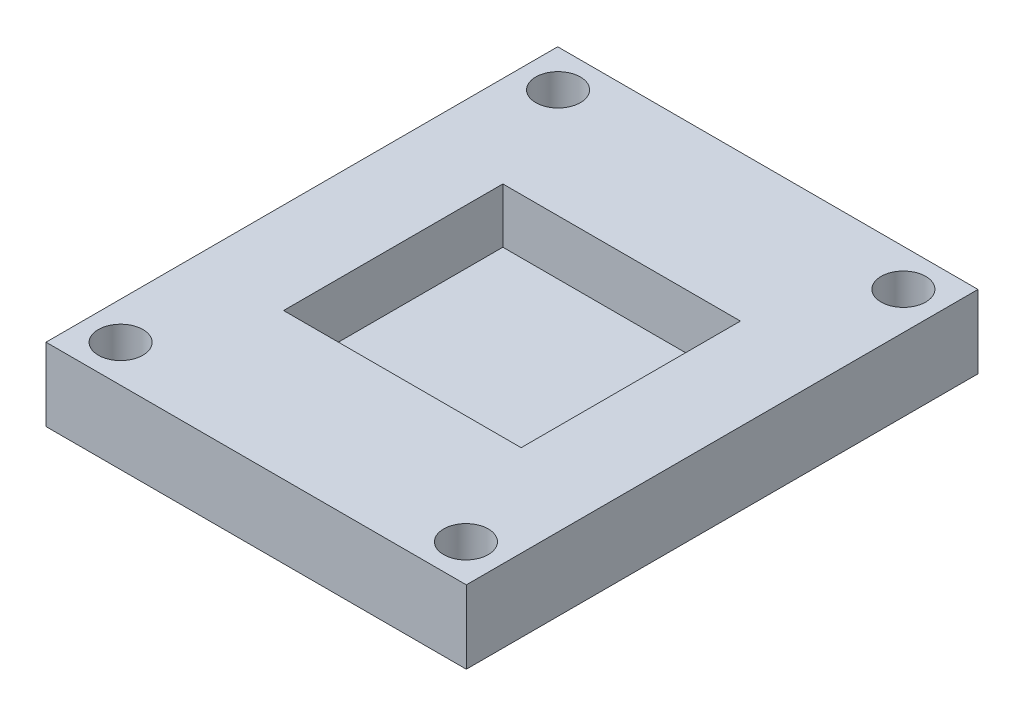
SolidWorks part; units mm, degrees
ref_plane "Front Plane" through (0, 0, 0) normal (0, 0, 1) x (1, 0, 0)
ref_plane "Top Plane" through (0, 0, 0) normal (0, 1, 0) x (1, 0, 0)
ref_plane "Right Plane" through (0, 0, 0) normal (1, 0, 0) x (0, 0, -1)
sketch "Sketch1" plane through (0, 0, 0) normal (0, 1, 0) x (1, 0, 0)
  line L0 (2.2113, 14.2748) -> (2.2113, -21.2852) construction
  line L1 (-12.3937, 14.2748) -> (16.8163, 14.2748)
  line L2 (-12.3937, 14.2748) -> (-12.3937, -21.2852)
  line L3 (-12.3937, -21.2852) -> (16.8163, -21.2852)
  line L4 (16.8163, 14.2748) -> (16.8163, -21.2852)
  line L5 (-12.3937, -3.5052) -> (16.8163, -3.5052) construction
  circle A0 centre (-9.7887, 11.6948) radius 1.55
  circle A1 centre (14.2113, 11.6948) radius 1.55
  circle A2 centre (14.2113, -18.7052) radius 1.55
  circle A3 centre (-9.7887, -18.7052) radius 1.55
  dimension "D3" = 3.1
  dimension "D4" = 3.1
  dimension "D5" = 3.1
  dimension "D6" = 3.1
  dimension "D1" = 29.21
  dimension "D2" = 35.56
  dimension "D7" = 24
  dimension "D8" = 30.4
  dimension "D9" = 15.2
  dimension "D10" = 12
extrude "Boss-Extrude1" add sketch "Sketch1" along normal blind 5.08
sketch "Sketch2" plane through (0, 5.08, 0) normal (0, 1, 0) x (1, 0, 0)
  line L0 (-12.3937, 14.2748) -> (-12.3937, -21.2852) construction
  line L1 (-6.0437, 4.1148) -> (10.4663, 4.1148)
  line L2 (-6.0437, 4.1148) -> (-6.0437, -11.1252)
  line L3 (-6.0437, -11.1252) -> (10.4663, -11.1252)
  line L4 (10.4663, 4.1148) -> (10.4663, -11.1252)
  line L5 (16.8163, -21.2852) -> (16.8163, 14.2748) construction
  line L6 (16.8163, 14.2748) -> (-12.3937, 14.2748) construction
  line L7 (-12.3937, -21.2852) -> (16.8163, -21.2852) construction
  dimension "D1" = 6.35
  dimension "D2" = 6.35
  dimension "D3" = 10.16
  dimension "D4" = 10.16
extrude "Cut-Extrude1" cut sketch "Sketch2" against normal blind 3.81
